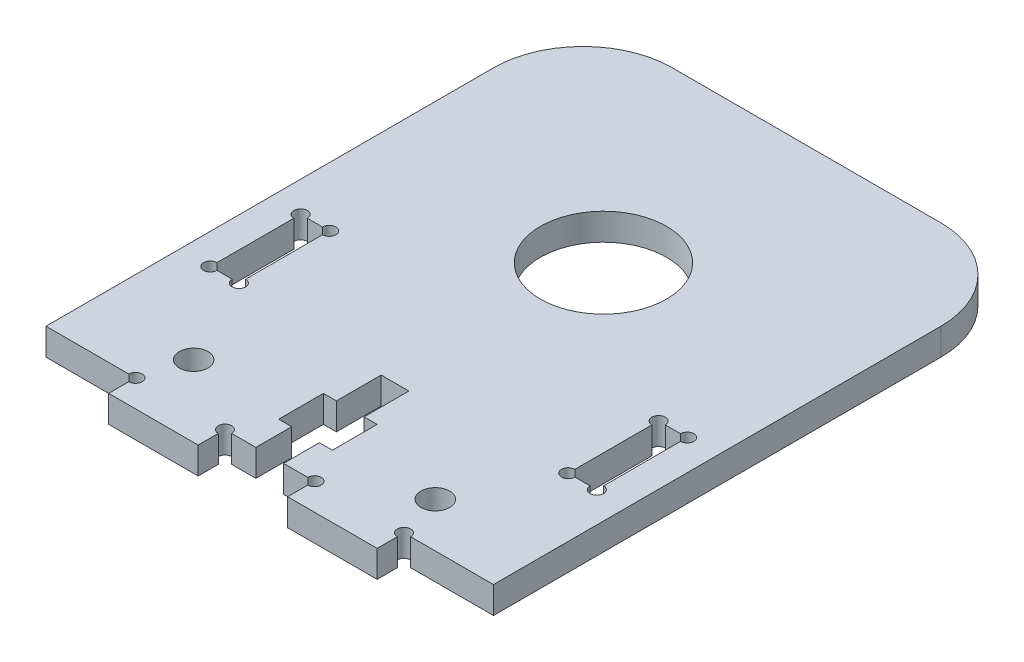
SolidWorks part; units mm, degrees
ref_plane "前视基准面" through (0, 0, 0) normal (0, 0, 1) x (1, 0, 0)
ref_plane "上视基准面" through (0, 0, 0) normal (0, 1, 0) x (1, 0, 0)
ref_plane "右视基准面" through (0, 0, 0) normal (1, 0, 0) x (0, 0, -1)
other "Configuration Table"
sketch "草图1" plane through (0, 0, 0) normal (0, 1, 0) x (1, 0, 0)
  line L1 (-25, -30) -> (25, -30)
  line L2 (-25, -30) -> (-25, 30)
  line L3 (-25, 30) -> (25, 30)
  line L4 (25, -30) -> (25, 30)
  line L5 (-25, -30) -> (25, 30) construction
  line L6 (-25, 30) -> (25, -30) construction
  point P0 (0, 0)
  dimension "D1" = 50
  dimension "D2" = 60
extrude "凸台-拉伸1" add sketch "草图1" along normal blind 3
sketch "草图2" plane through (0, 3, 0) normal (0, 1, 0) x (1, 0, 0)
  line L0 (0, 0) -> (0, -45.2545) construction
  line L1 (-25, -30) -> (25, -30) construction
  line L2 (-15, -30) -> (-5, -30)
  line L3 (-15, -30) -> (-15, -33)
  line L4 (-15, -33) -> (-5, -33)
  line L5 (-5, -30) -> (-5, -33)
  line L6 (-10, -33) -> (-10, -30) construction
  line L7 (15, -33) -> (5, -33)
  line L8 (5, -30) -> (5, -33)
  line L9 (15, -30) -> (5, -30)
  line L10 (15, -30) -> (15, -33)
  dimension "D1" = 3
  dimension "D2" = 10
  dimension "D3" = 10
extrude "凸台-拉伸2" add sketch "草图2" against normal blind 3
sketch "草图3" plane through (0, 3, 0) normal (0, 1, 0) x (1, 0, 0)
  line L0 (0, 0) -> (0, -32.9862) construction
  line L1 (-1.55, -30) -> (-1.55, -26)
  line L2 (-5, -30) -> (5, -30) construction
  line L3 (-1.55, -26) -> (-3, -26)
  line L4 (-3, -26) -> (-3, -21)
  line L5 (-3, -21) -> (-1.55, -21)
  line L6 (-1.55, -21) -> (-1.55, -16)
  line L7 (-1.55, -16) -> (1.55, -16)
  line L8 (-1.55, -30) -> (1.55, -30)
  line L9 (1.55, -30) -> (1.55, -26)
  line L10 (1.55, -26) -> (3, -26)
  line L11 (3, -26) -> (3, -21)
  line L12 (3, -21) -> (1.55, -21)
  line L13 (1.55, -21) -> (1.55, -16)
  point P12 (0, -30)
  point P19 (0, -16)
  dimension "D1" = 5
  dimension "D2" = 4
  dimension "D3" = 5
  dimension "D4" = 3
  dimension "D5" = 3.1
  dimension "D6" = 3.1
extrude "切除-拉伸1" cut sketch "草图3" against normal through all
sketch "草图4" plane through (0, 3, 0) normal (0, 1, 0) x (1, 0, 0)
  circle A0 centre (0, 7.2902) radius 7.05
  dimension "D1" = 14.1
extrude "切除-拉伸2" cut sketch "草图4" against normal through all
sketch "草图5" plane through (0, 0, 0) normal (0, -1, 0) x (1, 0, 0)
  line L0 (0, 0) -> (0, -3.0079) construction
  line L1 (20, 15.05) -> (20, 4.95) construction
  line L2 (18.4, 15.05) -> (21.6, 15.05)
  line L3 (18.4, 15.05) -> (18.4, 4.95)
  line L4 (18.4, 4.95) -> (21.6, 4.95)
  line L5 (21.6, 15.05) -> (21.6, 4.95)
  line L6 (18.4, 10) -> (21.6, 10) construction
  line L7 (25, 30) -> (25, -30) construction
  line L8 (15, 30) -> (25, 30) construction
  line L9 (-18.4, 4.95) -> (-21.6, 4.95)
  line L10 (-21.6, 15.05) -> (-21.6, 4.95)
  line L11 (-18.4, 15.05) -> (-21.6, 15.05)
  line L12 (-18.4, 15.05) -> (-18.4, 4.95)
  circle A0 centre (13.5, 25) radius 1.6
  circle A1 centre (-13.5, 25) radius 1.6
  point P13 (20, 10)
  dimension "D5" = 3.2
  dimension "D1" = 10.1
  dimension "D2" = 3.2
  dimension "D3" = 5
  dimension "D4" = 20
  dimension "D6" = 5
  dimension "D7" = 6.5
extrude "切除-拉伸3" cut sketch "草图5" against normal through all
sketch "草图7" plane through (0, 0, 0) normal (0, -1, 0) x (1, 0, 0)
  line L0 (0, 0) -> (0, 5.9238) construction
  circle A0 centre (-21.6, 15.05) radius 0.75
  circle A1 centre (-18.4, 15.05) radius 0.75
  circle A2 centre (-18.4, 4.95) radius 0.75
  circle A3 centre (-21.6, 4.95) radius 0.75
  circle A4 centre (21.6, 4.95) radius 0.75
  circle A5 centre (18.4, 4.95) radius 0.75
  circle A6 centre (18.4, 15.05) radius 0.75
  circle A7 centre (21.6, 15.05) radius 0.75
  circle A8 centre (-15, 30) radius 0.75
  circle A9 centre (-5, 30) radius 0.75
  circle A10 centre (5, 30) radius 0.75
  circle A11 centre (15, 30) radius 0.75
  dimension "D1" = 1.5
  dimension "D2" = 1.5
extrude "切除-拉伸4" cut sketch "草图7" against normal through all
fillet "圆角1" radius 10 2 edges at (25, 1.5, -30) (-25, 1.5, -30)
